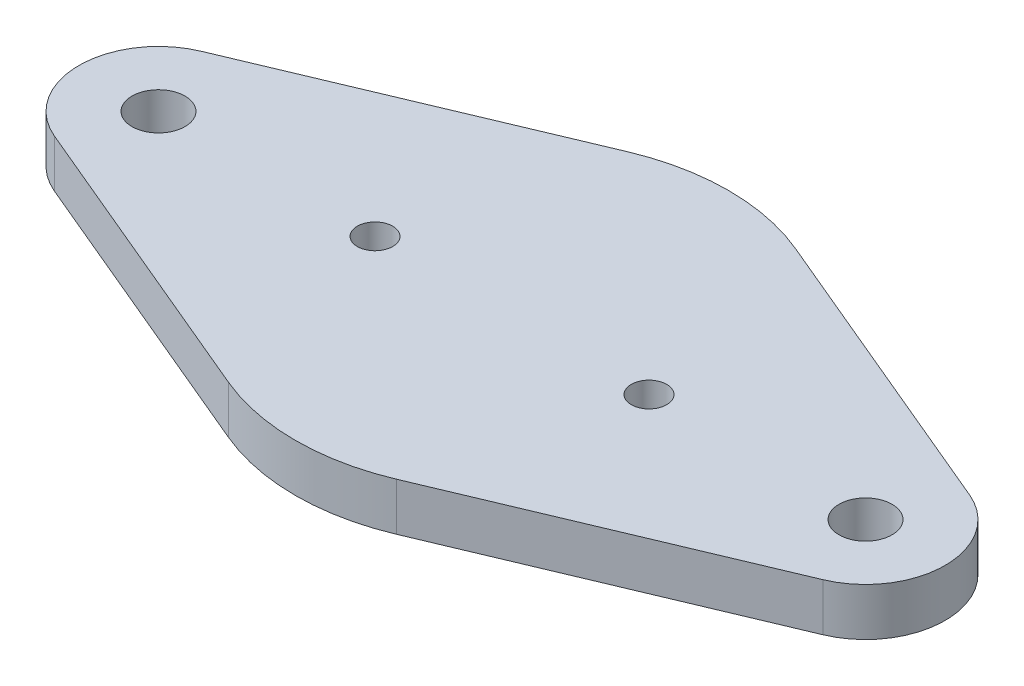
SolidWorks part; units mm, degrees
material "ABS PC"
ref_plane "Front Plane" through (0, 0, 0) normal (0, 0, 1) x (1, 0, 0)
ref_plane "Top Plane" through (0, 0, 0) normal (0, 1, 0) x (1, 0, 0)
ref_plane "Right Plane" through (0, 0, 0) normal (1, 0, 0) x (0, 0, -1)
sketch "Sketch1" plane through (0, 0, 0) normal (0, 1, 0) x (1, 0, 0)
  line L0 (4.7469, 11.2929) -> (21.7437, 4.1484)
  line L1 (21.7437, -4.1484) -> (4.7469, -11.2929)
  line L2 (-4.7469, 11.2929) -> (-21.7437, 4.1484)
  line L3 (-21.7437, -4.1484) -> (-4.7469, -11.2929)
  arc A0 (-4.7469, -11.2929) -> (4.7469, -11.2929) centre (0, 0) ccw
  arc A1 (21.7437, -4.1484) -> (21.7437, 4.1484) centre (20, 0) ccw
  arc A2 (-21.7437, 4.1484) -> (-21.7437, -4.1484) centre (-20, 0) ccw
  arc A3 (4.7469, 11.2929) -> (-4.7469, 11.2929) centre (0, 0) ccw
  dimension "D1" = 24.5
  dimension "D2" = 9
  dimension "D3" = 9
  dimension "D7" = 4.5
  dimension "D8" = 12.25
  dimension "D9" = 4.5
  dimension "D4" = 20
  dimension "D5" = 20
  dimension "D6" = 20
extrude "Boss-Extrude1" add sketch "Sketch1" along normal blind 2.7
sketch "Sketch2" plane through (0, 2.7, 0) normal (0, 1, 0) x (1, 0, 0)
  circle A0 centre (-20, 0) radius 1.5
  circle A1 centre (20, 0) radius 1.5
  circle A2 centre (7.75, 0) radius 1
  circle A3 centre (-7.75, 0) radius 1
  dimension "D1" = 3
  dimension "D2" = 3
  dimension "D3" = 2
  dimension "D4" = 2
  dimension "D5" = 7.75
  dimension "D6" = 7.75
extrude "Cut-Extrude1" cut sketch "Sketch2" against normal up to next
